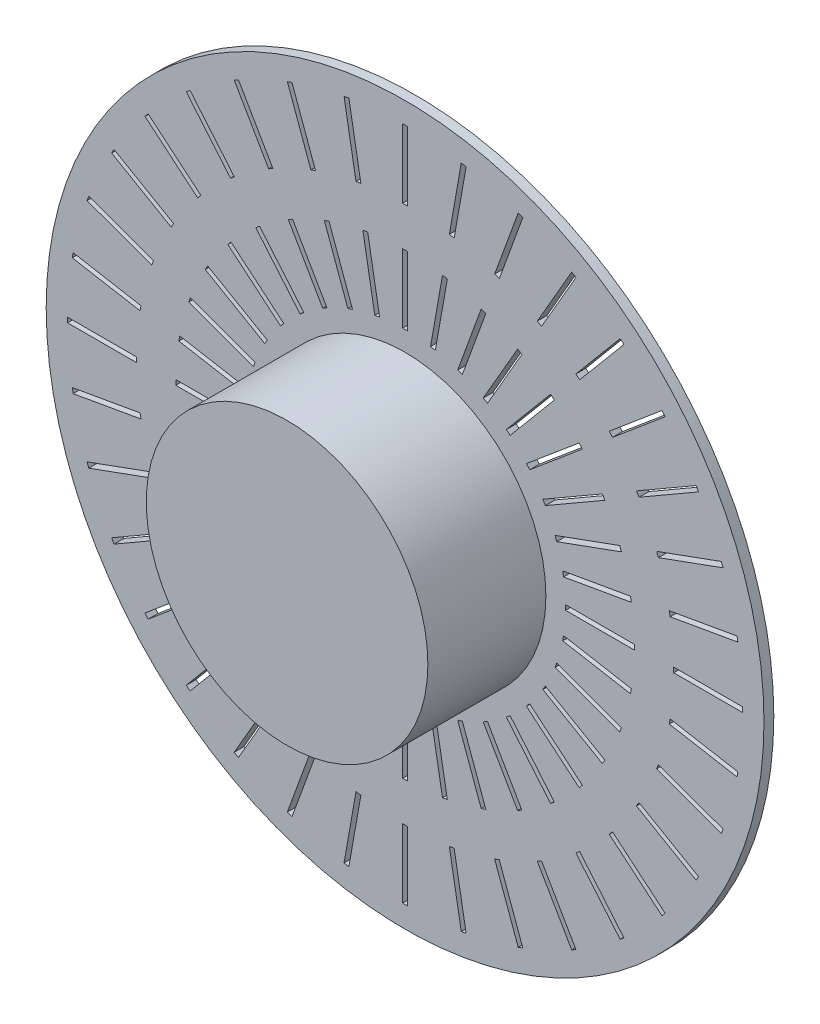
SolidWorks part; units mm, degrees
material "Plastique personnalisé"
ref_plane "Plan de face" through (0, 0, 0) normal (0, 0, 1) x (1, 0, 0)
ref_plane "Plan de dessus" through (0, 0, 0) normal (0, 1, 0) x (1, 0, 0)
ref_plane "Plan de droite" through (0, 0, 0) normal (1, 0, 0) x (0, 0, -1)
sketch "Esquisse1" plane through (0, 0, 0) normal (0, 0, 1) x (1, 0, 0)
  circle A0 centre (0, 0) radius 365
  dimension "D1" = 730
extrude "Boss.-Extru.1" add sketch "Esquisse1" along normal blind 10
sketch "Esquisse2" plane through (0, 0, 10) normal (0, 0, 1) x (1, 0, 0)
  circle A0 centre (0, 0) radius 143.2
  dimension "D1" = 286.4
extrude "Boss.-Extru.2" add sketch "Esquisse2" along normal blind 120
sketch "Esquisse4" plane through (0, 0, 10) normal (0, 0, 1) x (1, 0, 0)
  line L0 (-2.5, -233.2) -> (-2.5, -163.2)
  line L1 (-2.5, -233.2) -> (2.5, -233.2)
  line L2 (-2.5, -163.2) -> (2.5, -163.2)
  line L3 (2.5, -233.2) -> (2.5, -163.2)
  line L4 (-2.5, -233.2) -> (2.5, -163.2) construction
  line L5 (-2.5, -163.2) -> (2.5, -233.2) construction
  line L7 (-2.5, -273.2) -> (2.5, -273.2)
  line L8 (-2.5, -273.2) -> (-2.5, -343.2)
  line L9 (-2.5, -343.2) -> (2.5, -343.2)
  line L10 (2.5, -273.2) -> (2.5, -343.2)
  circle A0 centre (0, 0) radius 143.2 construction
  point P1 (0, -198.2)
  dimension "D2" = 198.2
  dimension "D1" = 70
  dimension "D3" = 5
  dimension "D4" = 70
  dimension "D5" = 40
extrude "Enlèv. mat.-Extru.1" cut sketch "Esquisse4" against normal through all contours L10 L7 L8 L9 | L0 L2 L3 L1
pattern_circular "Répétition circulaire1" count 36 over 360 about axis through (0, 0, 0) along (0, 0, 1) of "Enlèv. mat.-Extru.1"
